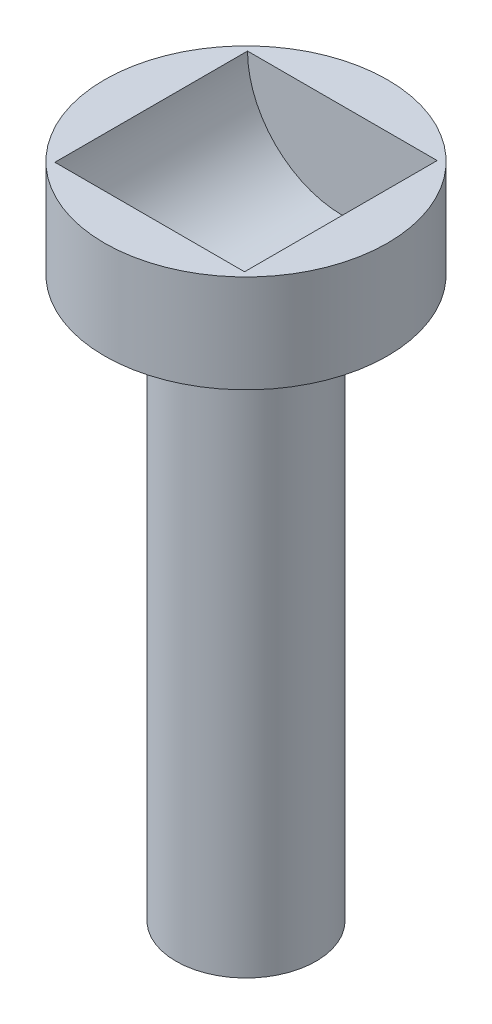
SolidWorks part; units mm, degrees
ref_plane "Front Plane" through (0, 0, 0) normal (0, 0, 1) x (1, 0, 0)
ref_plane "Top Plane" through (0, 0, 0) normal (0, 1, 0) x (1, 0, 0)
ref_plane "Right Plane" through (0, 0, 0) normal (1, 0, 0) x (0, 0, -1)
sketch "Sketch1" plane through (0, 0, 0) normal (0, 1, 0) x (1, 0, 0)
  circle A0 centre (0, 0) radius 2.4
  dimension "D1" = 4.8
extrude "Boss-Extrude1" add sketch "Sketch1" along normal blind 20
sketch "Sketch2" plane through (0, 0, 0) normal (0, -1, 0) x (1, 0, 0)
  circle A0 centre (0, 0) radius 1.195
  dimension "D1" = 2.39
extrude "Cut-Extrude1" cut sketch "Sketch2" against normal blind 10
sketch "Sketch4" plane through (0, 20, 0) normal (0, 1, 0) x (1, 0, 0)
  circle A0 centre (0, 0) radius 4.85
  dimension "D1" = 9.7
extrude "Boss-Extrude2" add sketch "Sketch4" along normal blind 2.54
sketch "Sketch6" plane through (0, 22.54, 0) normal (0, 1, 0) x (1, 0, 0)
  circle A0 centre (0, 0) radius 4.85
  dimension "D1" = 9.7
extrude "Boss-Extrude3" add sketch "Sketch6" against normal blind 3.35
sketch "Sketch5" plane through (0, 0, 0) normal (0, 0, 1) x (1, 0, 0)
  line L0 (4.85, 22.54) -> (-4.85, 22.54) construction
  circle A0 centre (0, 22.54) radius 3.25
  dimension "D1" = 6.5
extrude "Cut-Extrude3" cut sketch "Sketch5" against normal blind 3.302 and the other way blind 3.3
